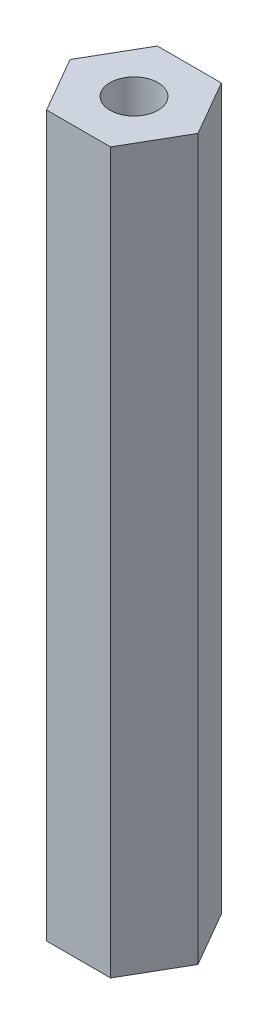
SolidWorks part; units mm, degrees
ref_plane "前视基准面" through (0, 0, 0) normal (0, 0, 1) x (1, 0, 0)
ref_plane "上视基准面" through (0, 0, 0) normal (0, 1, 0) x (1, 0, 0)
ref_plane "右视基准面" through (0, 0, 0) normal (1, 0, 0) x (0, 0, -1)
sketch "草图1" plane through (0, 0, 0) normal (0, 1, 0) x (1, 0, 0)
  line L1 (4, 0) -> (2, 3.4641)
  line L2 (2, 3.4641) -> (-2, 3.4641)
  line L3 (-2, 3.4641) -> (-4, 0)
  line L4 (-4, 0) -> (-2, -3.4641)
  line L5 (-2, -3.4641) -> (2, -3.4641)
  line L6 (2, -3.4641) -> (4, 0)
  circle A0 centre (0, 0) radius 4 construction
extrude "凸台-拉伸1" add sketch "草图1" along normal blind 45
sketch "草图2" plane through (0, 45, 0) normal (0, 1, 0) x (1, 0, 0)
  circle A0 centre (0, 0) radius 1.5
  dimension "D1" = 3
extrude "切除-拉伸1" cut sketch "草图2" against normal blind 5
pattern_linear "阵列(线性)1" count 2 spacing 40 along (0, -1, 0) of "切除-拉伸1"
